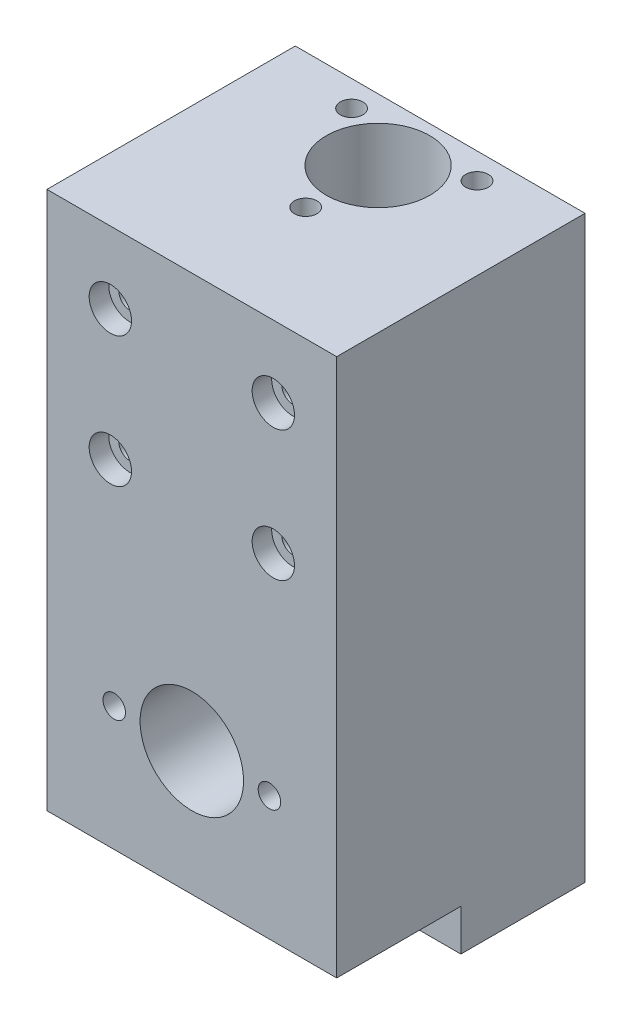
SolidWorks part; units mm, degrees
material "6061 Alloy"
ref_plane "Front Plane" through (0, 0, 0) normal (0, 0, 1) x (1, 0, 0)
ref_plane "Top Plane" through (0, 0, 0) normal (0, 1, 0) x (1, 0, 0)
ref_plane "Right Plane" through (0, 0, 0) normal (1, 0, 0) x (0, 0, -1)
sketch "Sketch1" plane through (0, 0, 0) normal (0, 1, 0) x (1, 0, 0)
  line L1 (-22.225, -19.05) -> (22.225, -19.05)
  line L2 (-22.225, -19.05) -> (-22.225, 19.05)
  line L3 (-22.225, 19.05) -> (22.225, 19.05)
  line L4 (22.225, -19.05) -> (22.225, 19.05)
  line L5 (-22.225, -19.05) -> (22.225, 19.05) construction
  line L6 (-22.225, 19.05) -> (22.225, -19.05) construction
  point P0 (0, 0)
  dimension "D1" = 44.45
  dimension "D2" = 38.1
extrude "Boss-Extrude1" add sketch "Sketch1" along normal blind 88.9
sketch "Sketch2" plane through (0, 0, 19.05) normal (0, 0, 1) x (1, 0, 0)
  line L0 (-22.225, 88.9) -> (-22.225, 0) construction
  line L1 (-22.225, 6.35) -> (22.225, 6.35)
  line L2 (-22.225, 6.35) -> (-22.225, 0)
  line L3 (-22.225, 0) -> (22.225, 0)
  line L4 (22.225, 6.35) -> (22.225, 0)
  dimension "D1" = 6.35
extrude "Cut-Extrude1" cut sketch "Sketch2" against normal blind 19.05
sketch "Sketch3" plane through (0, 88.9, 0) normal (0, 1, 0) x (1, 0, 0)
  line L0 (-22.225, 9.525) -> (22.225, 9.525) construction
  line L1 (-22.225, 19.05) -> (-22.225, -19.05) construction
  line L2 (22.225, -19.05) -> (22.225, 19.05) construction
  line L3 (22.225, 19.05) -> (-22.225, 19.05) construction
  circle A0 centre (0, 9.525) radius 7.9375
  dimension "D1" = 15.875
  dimension "D2" = 9.525
extrude "Cut-Extrude2" cut sketch "Sketch3" against normal up to next contours A0
hole_wizard "#8-32 Tapped Hole2" positions "Sketch5" profile "Sketch4" tap size "#8-32" standard "ANSI Inch"
sketch "Sketch5" plane through (0, 88.9, 0) normal (0, 1, 0) x (1, 0, 0)
  circle A0 centre (0, 9.525) radius 7.9375 construction
  point P0 (0, -1.5875)
  dimension "D1" = 11.1125
sketch "Sketch4" plane through (0, 88.9, 1.5875) normal (1, 0, 0) x (0, 0, 1)
  line L0 (0, 0) -> (0, 13.7378)
  line L1 (0, 13.7378) -> (1.7272, 12.7)
  line L2 (1.7272, 12.7) -> (1.7272, 0)
  line L5 (1.7272, 0) -> (0, 0)
  line L10 (0, 13.7378) -> (-1.7272, 12.7) construction
  line L11 (0, -6.35) -> (0, 107.95) construction
  dimension "Tap Drill Dia." = 3.4544
  dimension "Tap Drill Depth" = 12.7
  dimension "Drill Angle" = 118
cosmetic thread "Hole Thread1" parameters "D1"=9.525, "D2"=4.1656
pattern_circular "CirPattern1" count 3 over 360 about axis through (0, 0, -9.525) along (0, 1, 0) of "#8-32 Tapped Hole2"
hole_wizard "#6-32 Tapped Hole1" positions "Sketch7" profile "Sketch6" tap size "#6-32" standard "ANSI Inch"
sketch "Sketch7" plane through (0, 6.35, 0) normal (0, -1, 0) x (-1, 0, 0)
  line L0 (22.225, 0) -> (22.225, -19.05) construction
  line L1 (-22.225, -19.05) -> (22.225, -19.05) construction
  point P0 (17.4625, -14.2875)
  dimension "D1" = 4.7625
  dimension "D2" = 4.7625
sketch "Sketch6" plane through (-17.4625, 6.35, 14.2875) normal (1, 0, 0) x (0, 0, -1)
  line L0 (0, 0) -> (0, 18.5927)
  line L1 (0, 18.5927) -> (1.3525, 17.78)
  line L2 (1.3525, 17.78) -> (1.3525, 0)
  line L5 (1.3525, 0) -> (0, 0)
  line L10 (0, 18.5927) -> (-1.3526, 17.78) construction
  line L11 (0, -6.35) -> (0, 107.95) construction
  dimension "Tap Drill Dia." = 2.7051
  dimension "Tap Drill Depth" = 17.78
  dimension "Drill Angle" = 118
cosmetic thread "Hole Thread2" parameters "D1"=9.652, "D2"=3.5052
pattern_linear "LPattern1" count 2 spacing 9.525 along (0, 0, -1) count 2 spacing 34.925 along (1, 0, 0) of "#6-32 Tapped Hole1"
hole_wizard "CBORE for M3 SHCS1" positions "Sketch10" profile "Sketch8" counterbore size "M3" standard "ANSI Metric" end condition up to next
sketch "Sketch10" plane through (0, 0, 19.05) normal (0, 0, 1) x (1, 0, 0)
  line L0 (-22.225, 88.9) -> (-22.225, 6.35) construction
  line L1 (-22.225, 88.9) -> (22.225, 88.9) construction
  point P6 (-12.5, 77.9)
  dimension "D1" = 9.725
  dimension "D2" = 11
sketch "Sketch8" plane through (-12.5, 77.9, 19.05) normal (1, 0, 0) x (0, -1, 0)
  line L0 (0, 0) -> (0, 38.101)
  line L1 (0, 38.101) -> (1.7, 38.101)
  line L3 (1.7, 38.101) -> (1.7, 3)
  line L4 (1.7, 3) -> (3.25, 3)
  line L5 (3.25, 3) -> (3.25, 0)
  line L7 (3.25, 0) -> (0, 0)
  line L11 (0, -6.35) -> (0, 107.95) construction
  dimension "Thru Hole Dia." = 3.4
  dimension "Thru Hole Depth" = 38.101
  dimension "C'Bore Dia." = 6.5
  dimension "C'Bore Depth" = 3
sketch "Sketch11" plane through (0, 0, 19.05) normal (0, 0, 1) x (1, 0, 0)
  line L0 (22.225, 6.35) -> (-22.225, 6.35) construction
  line L1 (0, 25.4) -> (0, 6.35) construction
  line L2 (22.225, 6.35) -> (-22.225, 6.35) construction
  circle A0 centre (0, 25.4) radius 7.9375
  dimension "D1" = 15.875
  dimension "D2" = 19.05
extrude "Cut-Extrude3" cut sketch "Sketch11" against normal blind 12.7
hole_wizard "#8-32 Tapped Hole1" positions "Sketch13" profile "Sketch12" tap size "#8-32" standard "ANSI Inch"
sketch "Sketch13" plane through (0, 0, 19.05) normal (0, 0, 1) x (1, 0, 0)
  line L0 (-11.9062, 25.4) -> (11.9062, 25.4) construction
  circle A0 centre (0, 25.4) radius 7.9375 construction
  circle A1 centre (0, 25.4) radius 7.9375 construction
  point P0 (-11.9062, 25.4)
  point P3 (11.9062, 25.4)
  dimension "D1" = 23.8125
sketch "Sketch12" plane through (-11.9062, 25.4, 19.05) normal (1, 0, 0) x (0, -1, 0)
  line L0 (0, 0) -> (0, 20.0878)
  line L1 (0, 20.0878) -> (1.7272, 19.05)
  line L2 (1.7272, 19.05) -> (1.7272, 0)
  line L5 (1.7272, 0) -> (0, 0)
  line L10 (0, 20.0878) -> (-1.7272, 19.05) construction
  line L11 (0, -6.35) -> (0, 107.95) construction
  dimension "Tap Drill Dia." = 3.4544
  dimension "Tap Drill Depth" = 19.05
  dimension "Drill Angle" = 118
cosmetic thread "Hole Thread3" parameters "D1"=9.652, "D2"=4.1656
cosmetic thread "Hole Thread4" parameters "D1"=9.652, "D2"=4.1656
pattern_linear "LPattern2" count 2 spacing 25 along (1, 0, 0) count 2 spacing 20 along (0, -1, 0) of "CBORE for M3 SHCS1"
